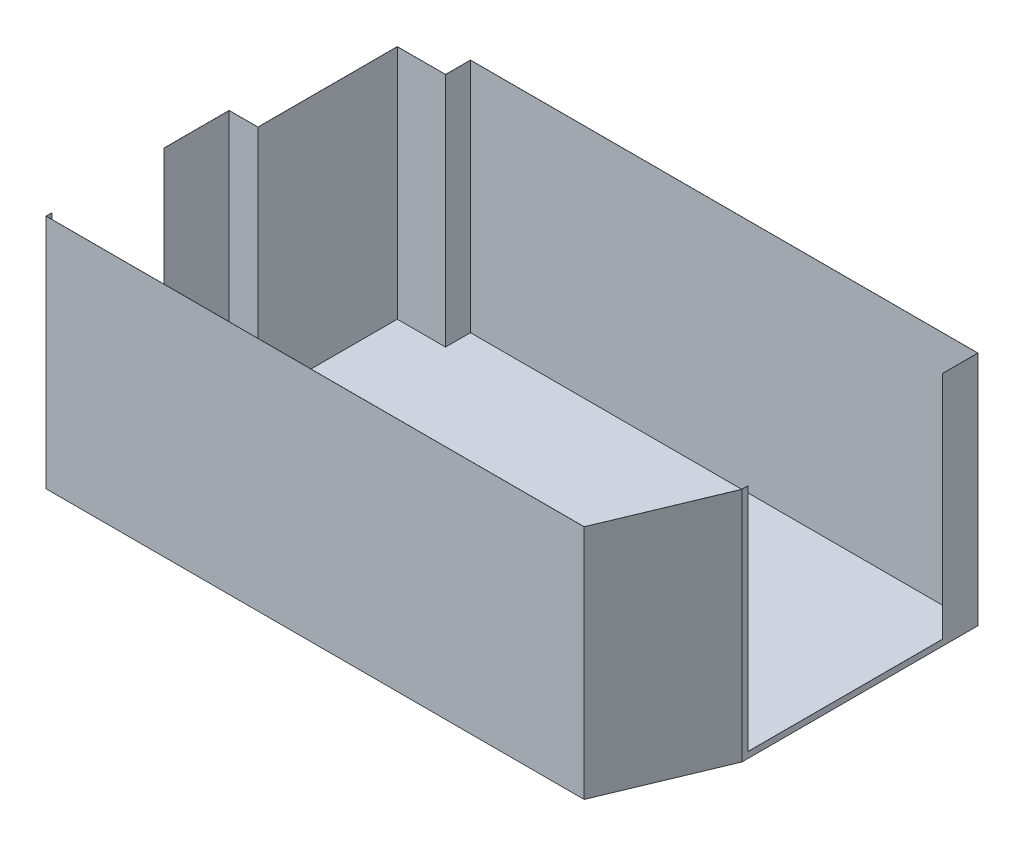
SolidWorks part; units mm, degrees
ref_plane "Front Plane" through (0, 0, 0) normal (0, 0, 1) x (1, 0, 0)
ref_plane "Top Plane" through (0, 0, 0) normal (0, 1, 0) x (1, 0, 0)
ref_plane "Right Plane" through (0, 0, 0) normal (1, 0, 0) x (0, 0, -1)
sketch "Sketch1" plane through (0, 0, 0) normal (0, 1, 0) x (1, 0, 0)
  line L1 (3000, -2500) -> (-3000, -2500)
  line L2 (3000, -2500) -> (3000, 2500)
  line L3 (3000, 2500) -> (-3000, 2500)
  line L4 (-3000, -2500) -> (-3000, 2500)
  line L5 (3000, -2500) -> (-3000, 2500) construction
  line L6 (3000, 2500) -> (-3000, -2500) construction
  point P0 (0, 0)
  dimension "D1" = 6000
  dimension "D2" = 5000
extrude "Boss-Extrude1" add sketch "Sketch1" along normal blind 1
sketch "Sketch2" plane through (0, 1, 0) normal (0, 1, 0) x (1, 0, 0)
  line L1 (-3000, -2500) -> (1560, -2500)
  line L2 (-3000, -2500) -> (-3000, -2499)
  line L3 (-3000, -2499) -> (1560, -2499)
  line L4 (1560, -2500) -> (1560, -2499)
  dimension "D1" = 4560
  dimension "D2" = 1
extrude "Boss-Extrude2" add sketch "Sketch2" along normal blind 2000
sketch "Sketch5" plane through (0, 1, 0) normal (0, 1, 0) x (1, 0, 0)
  line L1 (-3000, -2499) -> (-2999, -2499)
  line L2 (-3000, -2499) -> (-3000, -2449)
  line L3 (-3000, -2449) -> (-2999, -2449)
  line L4 (-2999, -2499) -> (-2999, -2449)
  dimension "D1" = 50
  dimension "D2" = 1
extrude "Boss-Extrude5" add sketch "Sketch5" along normal blind 2000
sketch "Sketch6" plane through (0, 1, 0) normal (0, 1, 0) x (1, 0, 0)
  line L0 (-3000, 2500) -> (-3000, -2449) construction
  line L1 (-3000, -1499) -> (-2999, -1499)
  line L2 (-3000, -1499) -> (-3000, -949)
  line L3 (-3000, -949) -> (-2999, -949)
  line L4 (-2999, -1499) -> (-2999, -949)
  line L5 (1560, -2499) -> (-2999, -2499) construction
  dimension "D1" = 1000
  dimension "D2" = 550
  dimension "D3" = 1
extrude "Boss-Extrude6" add sketch "Sketch6" along normal blind 2000
sketch "Sketch7" plane through (0, 1, 0) normal (0, 1, 0) x (1, 0, 0)
  line L1 (-3000, -949) -> (-2755, -949)
  line L2 (-3000, -949) -> (-3000, -948)
  line L3 (-3000, -948) -> (-2755, -948)
  line L4 (-2755, -949) -> (-2755, -948)
  point P5 (0, 0)
  point P6 (0, 0)
  point P7 (0, 0)
  point P8 (0, 0)
  dimension "D1" = 245
  dimension "D2" = 1
extrude "Boss-Extrude9" add sketch "Sketch7" along normal blind 2000
sketch "Sketch8" plane through (0, 1, 0) normal (0, 1, 0) x (1, 0, 0)
  line L1 (-2755, -948) -> (-2756, -948)
  line L2 (-2755, -948) -> (-2755, 232)
  line L3 (-2755, 232) -> (-2756, 232)
  line L4 (-2756, -948) -> (-2756, 232)
  dimension "D1" = 1180
  dimension "D2" = 1
extrude "Boss-Extrude10" add sketch "Sketch8" along normal blind 2000
sketch "Sketch9" plane through (0, 1, 0) normal (0, 1, 0) x (1, 0, 0)
  line L1 (-2756, 232) -> (-2346, 232)
  line L2 (-2756, 232) -> (-2756, 233)
  line L3 (-2756, 233) -> (-2346, 233)
  line L4 (-2346, 232) -> (-2346, 233)
  dimension "D1" = 410
  dimension "D2" = 1
extrude "Boss-Extrude11" add sketch "Sketch9" along normal blind 2000
sketch "Sketch10" plane through (0, 1, 0) normal (0, 1, 0) x (1, 0, 0)
  line L1 (-2346, 233) -> (-2347, 233)
  line L2 (-2346, 233) -> (-2346, 443)
  line L3 (-2346, 443) -> (-2347, 443)
  line L4 (-2347, 233) -> (-2347, 443)
  dimension "D1" = 210
  dimension "D2" = 1
extrude "Boss-Extrude12" add sketch "Sketch10" along normal blind 2000
sketch "Sketch11" plane through (0, 1, 0) normal (0, 1, 0) x (1, 0, 0)
  line L1 (-2347, 443) -> (1953, 443)
  line L2 (-2347, 443) -> (-2347, 444)
  line L3 (-2347, 444) -> (1953, 444)
  line L4 (1953, 443) -> (1953, 444)
  dimension "D1" = 4300
  dimension "D2" = 1
extrude "Boss-Extrude13" add sketch "Sketch11" along normal blind 2000
sketch "Sketch12" plane through (0, 1, 0) normal (0, 1, 0) x (1, 0, 0)
  line L1 (1953, 444) -> (1954, 444)
  line L2 (1953, 444) -> (1953, -1556)
  line L3 (1953, -1556) -> (1954, -1556)
  line L4 (1954, 444) -> (1954, -1556)
  dimension "D1" = 2000
  dimension "D2" = 1
extrude "Boss-Extrude14" add sketch "Sketch12" along normal blind 2000
sketch "Sketch13" plane through (0, 1, 0) normal (0, 1, 0) x (1, 0, 0)
  line L0 (1954, -1556) -> (1560, -2500)
  line L1 (1560, -2500) -> (3000, -2500) construction
  line L2 (1560, -2500) -> (1560, -2499)
  line L3 (1560, -2499) -> (1953, -1556)
  line L4 (1953, -1556) -> (1954, -1556)
  point P9 (0, 0)
extrude "Boss-Extrude16" add sketch "Sketch13" along normal blind 2000
sketch "Sketch14" plane through (1953, 0, 0) normal (-1, 0, 0) x (0, 0, 1)
  line L1 (1506, 51) -> (-144, 51)
  line L2 (1506, 51) -> (1506, 2051)
  line L3 (1506, 2051) -> (-144, 2051)
  line L4 (-144, 51) -> (-144, 2051)
  line L5 (1556, 2001) -> (1556, 1) construction
  line L7 (-443, 1) -> (1556, 1) construction
  point P10 (0, 0)
  dimension "D1" = 1650
  dimension "D2" = 50
  dimension "D3" = 50
  dimension "D4" = 2000
extrude "Cut-Extrude1" cut sketch "Sketch14" against normal through all
sketch "Sketch15" plane through (0, 1, 0) normal (0, 1, 0) x (1, 0, 0)
  line L0 (1560, -2500) -> (1954, -1556)
  line L1 (1560, -2500) -> (1954, -1556) construction
  line L2 (1954, -1556) -> (1954, 444) construction
  line L3 (1954, -1556) -> (1954, 444)
  line L4 (1954, 444) -> (-2347, 444)
  line L5 (-2347, 444) -> (-2347, 233)
  line L6 (-2347, 233) -> (-2756, 233)
  line L7 (-2756, 233) -> (-2756, -948)
  line L8 (-2756, -948) -> (-3000, -948)
  line L9 (-3000, -948) -> (-3000, 2500)
  line L10 (-3000, 2500) -> (3000, 2500)
  line L11 (3000, 2500) -> (3000, -2500)
  line L12 (3000, -2500) -> (1560, -2500)
extrude "Cut-Extrude2" cut sketch "Sketch15" against normal blind 2000
